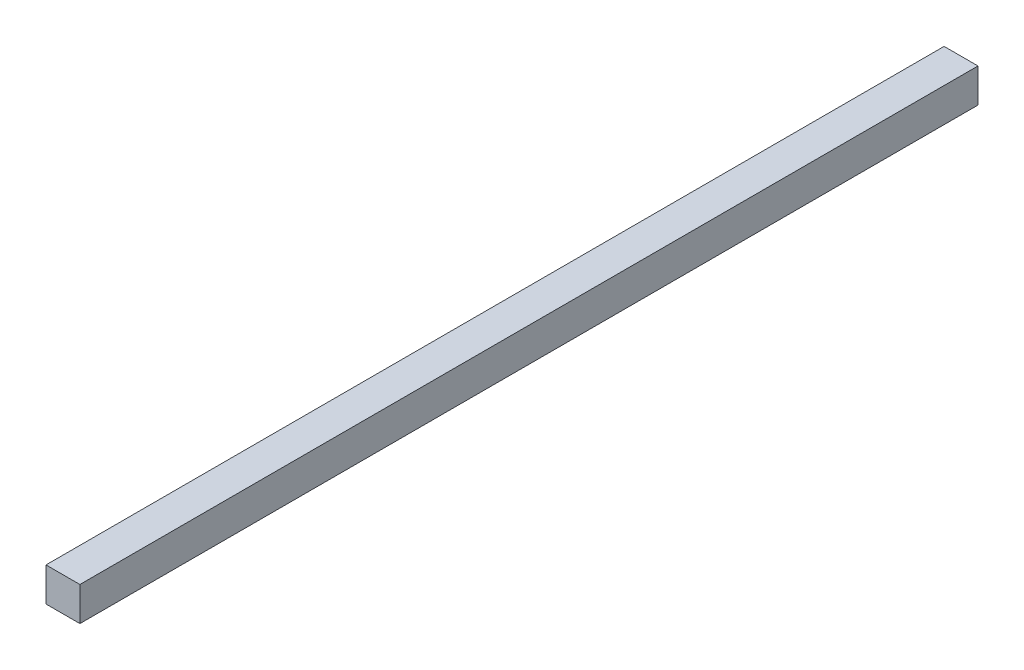
SolidWorks part; units mm, degrees
ref_plane "Plan de face" through (0, 0, 0) normal (0, 0, 1) x (1, 0, 0)
ref_plane "Plan de dessus" through (0, 0, 0) normal (0, 1, 0) x (1, 0, 0)
ref_plane "Plan de droite" through (0, 0, 0) normal (1, 0, 0) x (0, 0, -1)
sketch "Esquisse1" plane through (0, 0, 0) normal (0, 0, 1) x (1, 0, 0)
  line L1 (-5, -5) -> (5, -5)
  line L2 (-5, -5) -> (-5, 5)
  line L3 (-5, 5) -> (5, 5)
  line L4 (5, -5) -> (5, 5)
extrude "Entretoise_265mm" add sketch "Esquisse1" against normal blind 265
